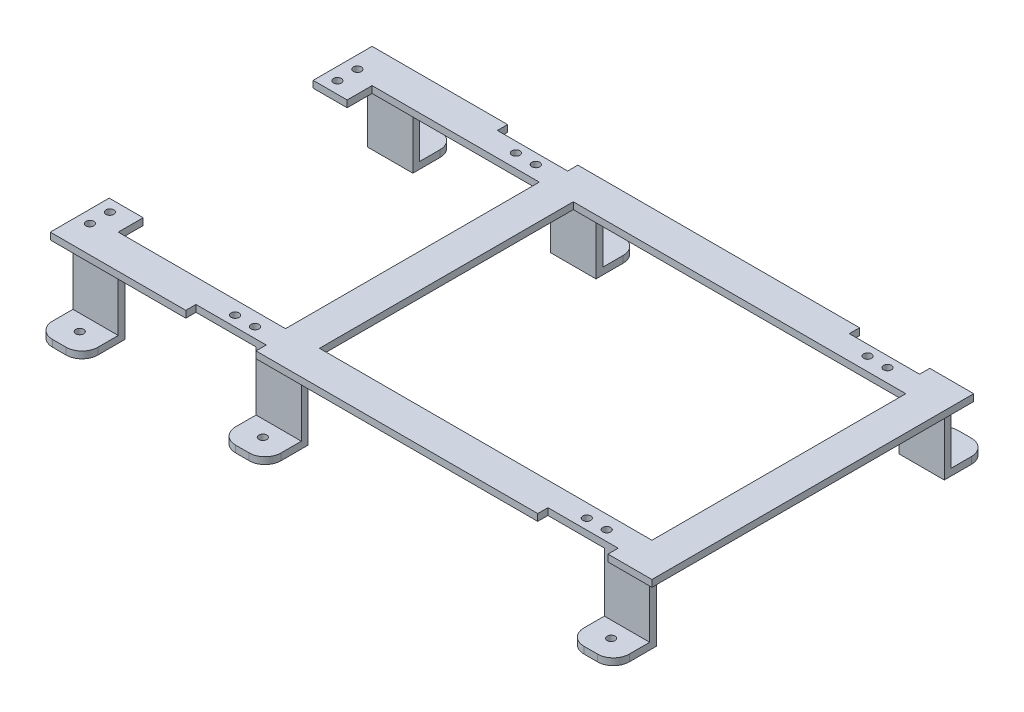
SolidWorks part; units mm, degrees
material "Acrílico (Impacto medio-alto)"
ref_plane "Alzado" through (0, 0, 0) normal (0, 0, 1) x (1, 0, 0)
ref_plane "Planta" through (0, 0, 0) normal (0, 1, 0) x (1, 0, 0)
ref_plane "Vista lateral" through (0, 0, 0) normal (1, 0, 0) x (0, 0, -1)
sketch "Croquis1" plane through (0, 0, 0) normal (0, 1, 0) x (1, 0, 0)
  line L0 (117.75, 56) -> (-117.75, 56)
  line L1 (132.75, -71) -> (-132.75, -71)
  line L2 (132.75, -71) -> (132.75, 71)
  line L3 (132.75, 71) -> (-132.75, 71)
  line L4 (-132.75, -71) -> (-132.75, 71)
  line L5 (132.75, -71) -> (-132.75, 71) construction
  line L6 (132.75, 71) -> (-132.75, -71) construction
  line L7 (-117.75, -56) -> (-117.75, 56)
  line L8 (117.75, -56) -> (-117.75, -56)
  line L9 (117.75, -56) -> (117.75, 56)
  point P0 (0, 0)
  dimension "D1" = 142
  dimension "D2" = 265.5
  dimension "D3" = 15
extrude "Saliente-Extruir1" add sketch "Croquis1" along normal blind 3
ref_plane "Plano1" through (-127.25, 0, 0) normal (1, 0, 0) x (0, 0, -1)
sketch "Croquis2" plane through (-127.25, 0, 0) normal (-1, 0, 0) x (0, 0, 1)
  line L0 (66.5, 0) -> (66.5, -26)
  line L6 (63.5, 0) -> (66.5, 0)
  line L8 (82.5, -29) -> (82.5, -26)
  line L9 (82.5, -26) -> (66.5, -26)
  line L20 (63.5, 0) -> (63.5, -29)
  line L21 (63.5, -29) -> (82.5, -29)
  line L22 (71, 3) -> (71, 0) construction
  line L23 (-71, 0) -> (71, 0) construction
  dimension "D1" = 29
  dimension "D2" = 3
  dimension "D3" = 4.5
  dimension "D4" = 19
  dimension "D5" = 3
extrude "Saliente-Extruir2" add sketch "Croquis2" against normal blind 20
mirror "Simetría1" about plane through (0, 0, 0) normal (1, 0, 0) of "Saliente-Extruir2"
mirror "Simetría2" about plane through (0, 0, 0) normal (0, 0, 1) of "Simetría1", "Saliente-Extruir2"
sketch "Croquis3" plane through (0, 3, 0) normal (0, 1, 0) x (1, 0, 0)
  line L1 (-120, 32.5) -> (-60, 32.5)
  line L2 (-120, 32.5) -> (-120, -32.5)
  line L3 (-120, -32.5) -> (-60, -32.5)
  line L4 (-60, 32.5) -> (-60, -32.5)
  point P4 (-60, 0)
  dimension "D1" = 65
  dimension "D2" = 60
  dimension "D3" = 60
extrude "Cortar-Extruir1" [suppressed] cut sketch "Croquis3" against normal through all
mirror "Simetría3" [suppressed] about plane through (0, 0, 0) normal (1, 0, 0)
ref_plane "Plano2" through (-36.45, 0, 0) normal (1, 0, 0) x (0, 0, -1)
sketch "Croquis4" plane through (-36.45, 0, 0) normal (1, 0, 0) x (0, 0, -1)
  line L12 (-63.5, 0) -> (-66.5, 0)
  line L13 (-66.5, 0) -> (-66.5, -26)
  line L14 (-66.5, -26) -> (-82.5, -26)
  line L15 (-82.5, -26) -> (-82.5, -29)
  line L16 (-82.5, -29) -> (-63.5, -29)
  line L17 (-82.5, -29) -> (-63.5, -29)
  line L19 (-66.5, 0) -> (-66.5, -26)
  line L20 (-66.5, -26) -> (-82.5, -26)
  line L21 (-82.5, -26) -> (-82.5, -29)
  line L28 (-63.5, 0) -> (-66.5, 0)
  line L38 (-63.5, -29) -> (-63.5, 0)
  line L40 (-63.5, -29) -> (-63.5, 0)
  dimension "D1" = 0
extrude "Saliente-Extruir3" add sketch "Croquis4" along normal mid plane 20
mirror "Simetría4" about plane through (0, 0, 0) normal (0, 0, 1) of "Saliente-Extruir3"
sketch "Croquis5" plane through (0, 3, 0) normal (0, 1, 0) x (1, 0, 0)
  line L1 (-105.499, -45) -> (-143.7054, -45)
  line L2 (-105.499, -45) -> (-105.499, 45)
  line L3 (-105.499, 45) -> (-143.7054, 45)
  line L4 (-143.7054, -45) -> (-143.7054, 45)
  line L5 (-105.499, -45) -> (-143.7054, 45) construction
  line L6 (-105.499, 45) -> (-143.7054, -45) construction
  point P0 (-124.6022, 0)
  dimension "D1" = 90
extrude "Cortar-Extruir2" cut sketch "Croquis5" against normal through all
sketch "Croquis7" plane through (0, 3, 0) normal (0, 1, 0) x (1, 0, 0)
  line L1 (-49.2, 56) -> (-23.2245, 56)
  line L2 (-49.2, 56) -> (-49.2, -56)
  line L3 (-49.2, -56) -> (-23.2245, -56)
  line L4 (-23.2245, 56) -> (-23.2245, -56)
extrude "Cortar-Extruir3" [suppressed] cut sketch "Croquis7" against normal through all
sketch "Croquis6" plane through (0, 3, 0) normal (0, 1, 0) x (1, 0, 0)
  line L0 (-36.45, 56) -> (-36.45, -56) construction
  line L1 (117.75, 56) -> (-117.75, 56) construction
  line L2 (-117.75, -56) -> (117.75, -56) construction
  line L4 (-132.75, 71) -> (-132.75, 45) construction
  line L6 (-43.95, 56) -> (-28.95, 56)
  line L7 (-43.95, 56) -> (-43.95, -56)
  line L8 (-43.95, -56) -> (-28.95, -56)
  line L9 (-28.95, 56) -> (-28.95, -56)
  point P12 (-36.45, 56)
  point P13 (-36.45, -56)
  dimension "D1" = 96.3
  dimension "D2" = 15
extrude "Saliente-Extruir4" add sketch "Croquis6" against normal up to surface (3 mm away) up to face at (-36.45, 0, -65)
sketch "Croquis8" plane through (0, 3, 0) normal (0, 1, 0) x (1, 0, 0)
  line L0 (132.75, 71) -> (-132.75, 71) construction
  line L1 (113.35, 66.5) -> (82.35, 66.5)
  line L2 (113.35, 66.5) -> (113.35, 71)
  line L3 (113.35, 71) -> (82.35, 71)
  line L4 (82.35, 66.5) -> (82.35, 71)
  line L5 (132.75, -71) -> (132.75, 71) construction
  line L6 (-132.75, 71) -> (-132.75, 45) construction
  line L7 (-41.95, 66.5) -> (-72.95, 66.5)
  line L8 (-41.95, 66.5) -> (-41.95, 71)
  line L9 (-41.95, 71) -> (-72.95, 71)
  line L10 (-72.95, 66.5) -> (-72.95, 71)
  dimension "D1" = 4.5
  dimension "D2" = 19.4
  dimension "D3" = 31
  dimension "D4" = 59.8
extrude "Cortar-Extruir4" cut sketch "Croquis8" against normal up to surface (3 mm away) up to face at (-68.7, 0, 0)
sketch "Croquis9" plane through (0, 3, 0) normal (0, 1, 0) x (1, 0, 0)
  circle A0 centre (-127.25, 59) radius 1.75
  circle A1 centre (-127.25, 50.2) radius 1.75
extrude "Cortar-Extruir5" cut sketch "Croquis9" against normal through all
sketch "Croquis11" plane through (0, 3, 0) normal (0, 1, 0) x (1, 0, 0)
  circle A0 centre (103.7509, 61.953) radius 1.75
  circle A1 centre (94.9509, 61.953) radius 1.75
extrude "Cortar-Extruir7" cut sketch "Croquis11" against normal blind 4
sketch "Croquis12" plane through (0, 3, 0) normal (0, 1, 0) x (1, 0, 0)
  circle A0 centre (-51.4491, 61.953) radius 1.75
  circle A1 centre (-60.2491, 61.953) radius 1.75
  dimension "D1" = 3.5
extrude "Cortar-Extruir8" cut sketch "Croquis12" against normal blind 4
mirror "Simetría5" about plane through (0, 0, 0) normal (0, 0, 1) of "Cortar-Extruir8", "Cortar-Extruir7", "Cortar-Extruir5"
mirror "Simetría6" about plane through (0, 0, 0) normal (0, 0, 1) of "Cortar-Extruir4"
fillet "Redondeo1" radius 7 2 edges at (-127.25, -27.5, 82.5) (-107.25, -27.5, 82.5)
fillet "Redondeo2" radius 7 4 edges at (-26.45, -27.5, 82.5) (-46.45, -27.5, 82.5) (127.25, -27.5, 82.5) (107.25, -27.5, 82.5)
sketch "Croquis13" plane through (0, -26, 0) normal (0, 1, 0) x (1, 0, 0)
  line L0 (-114.25, -82.5) -> (-120.25, -82.5) construction
  line L1 (-127.25, -75.5) -> (-127.25, -66.5) construction
  circle A0 centre (-117.25, -73.5) radius 1.75
  dimension "D2" = 3.5
  dimension "D1" = 9
  dimension "D3" = 10
extrude "Cortar-Extruir9" cut sketch "Croquis13" against normal through all
mirror "Simetría7" about plane through (0, 0, 0) normal (1, 0, 0) of "Cortar-Extruir9"
sketch "Croquis15" plane through (0, -26, 0) normal (0, 1, 0) x (1, 0, 0)
  line L0 (-46.45, -66.5) -> (-46.45, -75.5) construction
  line L1 (-33.45, -82.5) -> (-39.45, -82.5) construction
  circle A0 centre (-36.45, -73.5) radius 1.75
  dimension "D3" = 3.5
  dimension "D1" = 10
  dimension "D2" = 9
extrude "Cortar-Extruir10" cut sketch "Croquis15" against normal through all
mirror "Simetría12" about plane through (0, 0, 0) normal (0, 0, 1) of "Cortar-Extruir10", "Simetría7", "Cortar-Extruir9"
fillet "Redondeo3" radius 7 6 edges at (-127.25, -27.5, -82.5) (-107.25, -27.5, -82.5) (-46.45, -27.5, -82.5) (-26.45, -27.5, -82.5) (107.25, -27.5, -82.5) (127.25, -27.5, -82.5)
